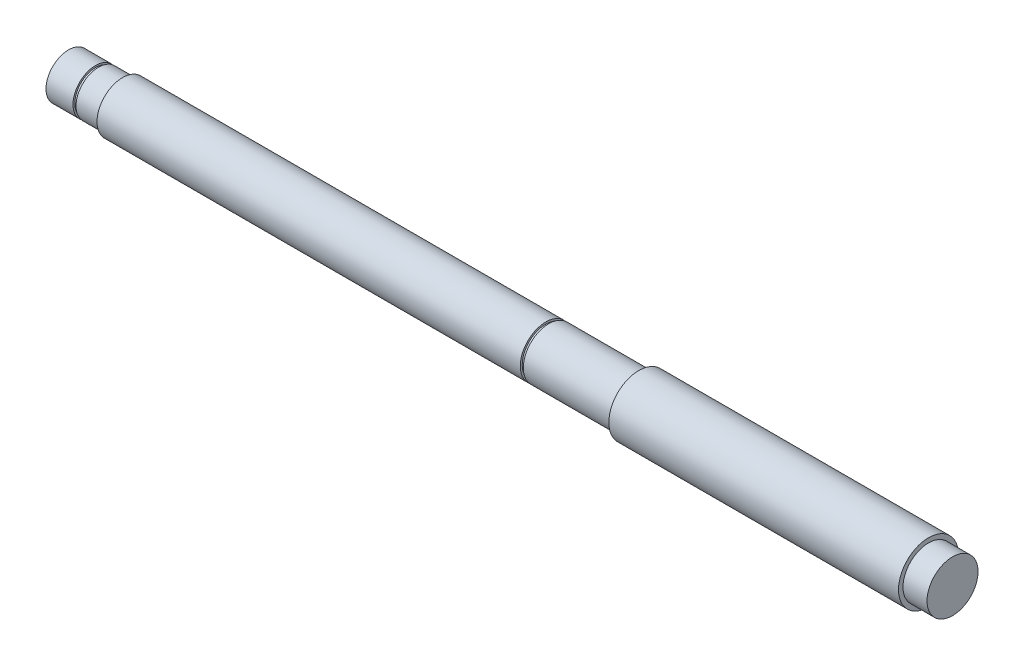
SolidWorks part; units mm, degrees
ref_plane "前视基准面" through (0, 0, 0) normal (0, 0, 1) x (1, 0, 0)
ref_plane "上视基准面" through (0, 0, 0) normal (0, 1, 0) x (1, 0, 0)
ref_plane "右视基准面" through (0, 0, 0) normal (1, 0, 0) x (0, 0, -1)
sketch "草图1" plane through (0, 0, 0) normal (0, 1, 0) x (1, 0, 0)
  line L0 (-79.5608, 0) -> (76.3736, 0) construction
  line L1 (0, 0) -> (0, 7.5)
  line L2 (0, 7.5) -> (9, 7.5)
  line L3 (9, 7.5) -> (9, 6.9)
  line L4 (9, 6.9) -> (10, 6.9)
  line L5 (10, 6.9) -> (10, 7.5)
  line L6 (10, 7.5) -> (18, 7.5)
  line L7 (18, 7.5) -> (18, 8.5)
  line L8 (18, 8.5) -> (159, 8.5)
  line L9 (159, 8.5) -> (159, 7.85)
  line L10 (159, 7.85) -> (160, 7.85)
  line L11 (160, 7.85) -> (160, 8.5)
  line L12 (160, 8.5) -> (190, 8.5)
  line L13 (190, 8.5) -> (190, 10)
  line L14 (190, 10) -> (286.5, 10)
  line L15 (286.5, 10) -> (286.5, 8.5)
  line L16 (286.5, 8.5) -> (294.5, 8.5)
  line L17 (294.5, 8.5) -> (294.5, 0)
  line L18 (0, 0) -> (294.5, 0)
revolve "旋转1" add sketch "草图1" angle 360 about L0
